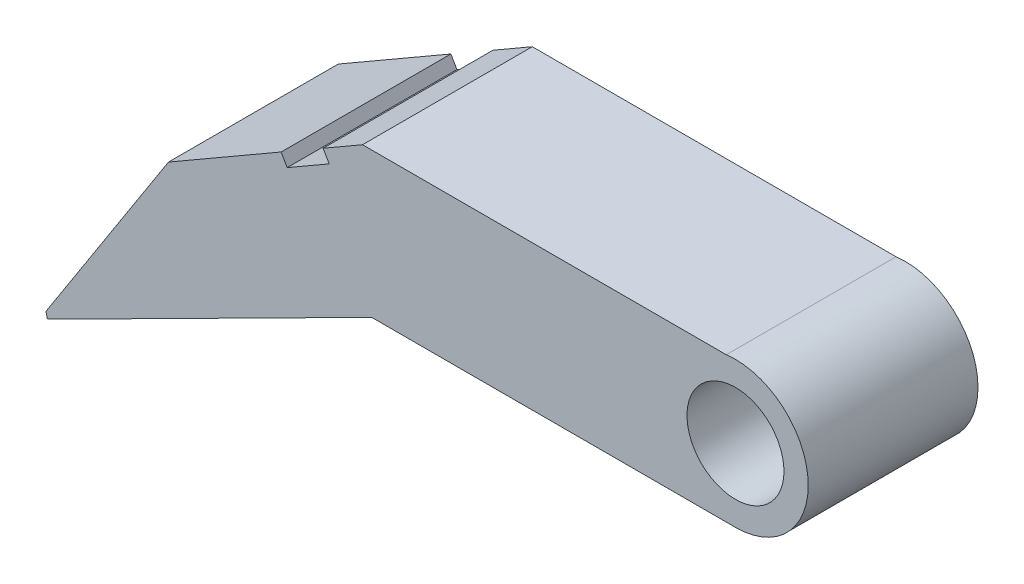
SolidWorks part; units mm, degrees
material "海绵橡胶板 HM101(膨胀)"
ref_plane "前视基准面" through (0, 0, 0) normal (0, 0, 1) x (1, 0, 0)
ref_plane "上视基准面" through (0, 0, 0) normal (0, 1, 0) x (1, 0, 0)
ref_plane "右视基准面" through (0, 0, 0) normal (1, 0, 0) x (0, 0, -1)
sketch "草图1" plane through (0, 0, 0) normal (0, 0, 1) x (1, 0, 0)
  circle A0 centre (0, 0) radius 2
  circle A1 centre (0, 0) radius 3
  dimension "D1" = 4
  dimension "D2" = 6
extrude "凸台-拉伸1" add sketch "草图1" along normal blind 7
sketch "草图2" plane through (0, 0, 0) normal (0, 0, -1) x (-1, 0, 0)
  line L0 (0.3782, 2.9761) -> (15.3782, 2.9761)
  line L1 (0, -3) -> (15, -3)
  line L2 (15.3782, 2.9761) -> (23.3782, -1.6427)
  line L3 (23.3782, -1.6427) -> (28.6996, -9.918)
  line L4 (28.6996, -9.918) -> (15, -3)
  circle A0 centre (0, 0) radius 3 construction
  arc A1 (0.3782, 2.9761) -> (0, -3) centre (0, 0) ccw
  circle A2 centre (0, 0) radius 2
  dimension "D1" = 15
  dimension "D2" = 15
  dimension "D3" = 8
  dimension "D4" = 150
extrude "凸台-拉伸2" add sketch "草图2" against normal blind 7
chamfer "倒角1" distance 0.5 angle 45 1 edges at (-28.6996, -9.918, 3.5)
sketch "草图3" plane through (0, 0, 0) normal (0, 0, -1) x (-1, 0, 0)
  line L0 (15.3782, 2.9761) -> (0.3782, 2.9761) construction
  line L1 (10, 2.9761) -> (12, 2.9761)
  line L2 (10, 2.9761) -> (10, 2.4761)
  line L3 (10, 2.4761) -> (12, 2.4761)
  line L4 (12, 2.9761) -> (12, 2.4761)
  line L5 (17.0021, 2.0385) -> (16.7521, 1.6055)
  line L6 (23.3782, -1.6427) -> (15.3782, 2.9761) construction
  line L7 (16.7521, 1.6055) -> (18.4842, 0.6055)
  line L8 (18.4842, 0.6055) -> (18.7342, 1.0385)
  line L9 (18.7342, 1.0385) -> (17.0021, 2.0385)
  dimension "D1" = 2
  dimension "D2" = 0.5
  dimension "D3" = 10
  dimension "D4" = 0.5
  dimension "D5" = 2
extrude "切除-拉伸1" cut sketch "草图3" against normal blind 7
sketch "草图4" plane through (0, 2.4761, 0) normal (0, 1, 0) x (1, 0, 0)
  line L1 (-12, 0) -> (-10, 0)
  line L2 (-12, 0) -> (-12, -7)
  line L3 (-12, -7) -> (-10, -7)
  line L4 (-10, 0) -> (-10, -7)
extrude "凸台-拉伸3" add sketch "草图4" along normal blind 0.5
